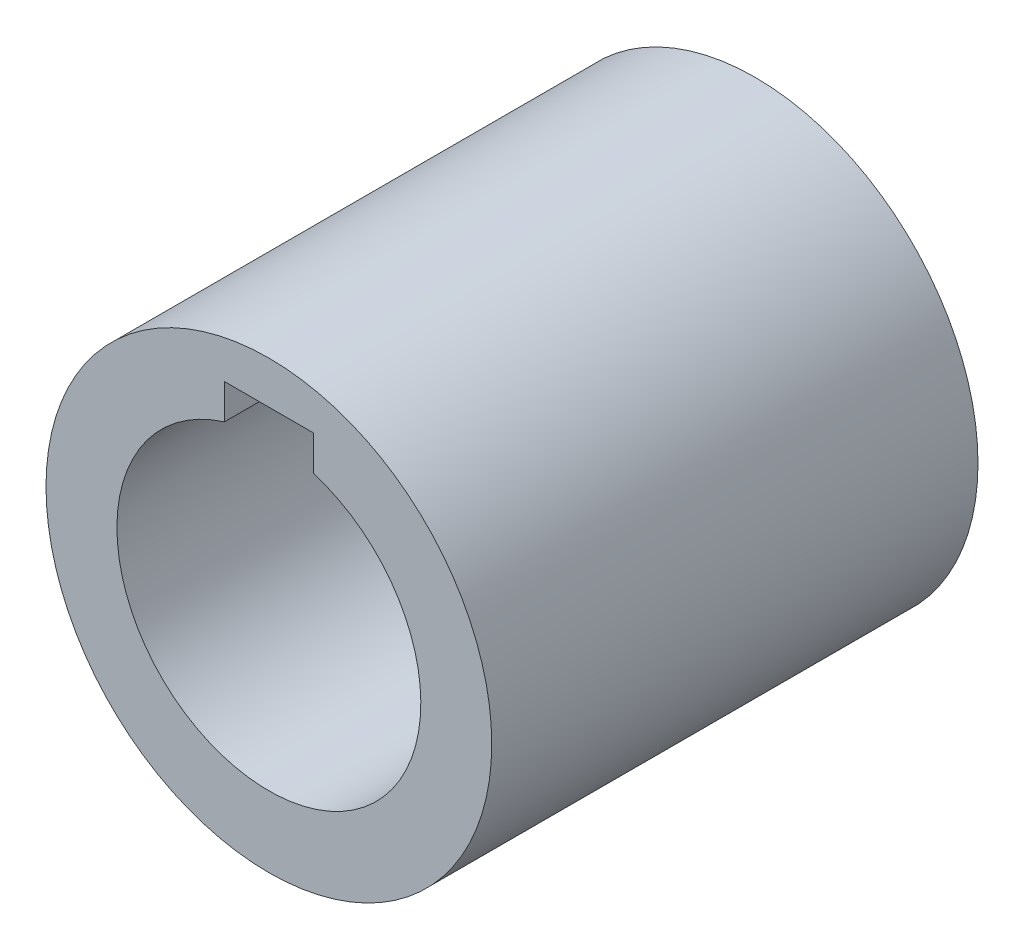
SolidWorks part; units mm, degrees
material "ASTM A36 Steel"
ref_plane "Front Plane" through (0, 0, 0) normal (0, 0, 1) x (1, 0, 0)
ref_plane "Top Plane" through (0, 0, 0) normal (0, 1, 0) x (1, 0, 0)
ref_plane "Right Plane" through (0, 0, 0) normal (1, 0, 0) x (0, 0, -1)
sketch "Sketch1" plane through (0, 0, 0) normal (0, 0, 1) x (1, 0, 0)
  circle A0 centre (0, 0) radius 55
  circle A1 centre (0, 0) radius 37.5
  dimension "D1" = 110
  dimension "D2" = 75
extrude "Boss-Extrude1" add sketch "Sketch1" along normal blind 120
sketch "Sketch2" plane through (0, 0, 120) normal (0, 0, 1) x (1, 0, 0)
  line L1 (-11, 30.5) -> (11, 30.5)
  line L2 (-11, 30.5) -> (-11, 44.5)
  line L3 (-11, 44.5) -> (11, 44.5)
  line L4 (11, 30.5) -> (11, 44.5)
  line L5 (-11, 30.5) -> (11, 44.5) construction
  line L6 (-11, 44.5) -> (11, 30.5) construction
  circle A0 centre (0, 0) radius 37.5 construction
  point P0 (0, 37.5)
  dimension "D1" = 14
  dimension "D2" = 22
extrude "Cut-Extrude1" cut sketch "Sketch2" against normal through all both and the other way through all
